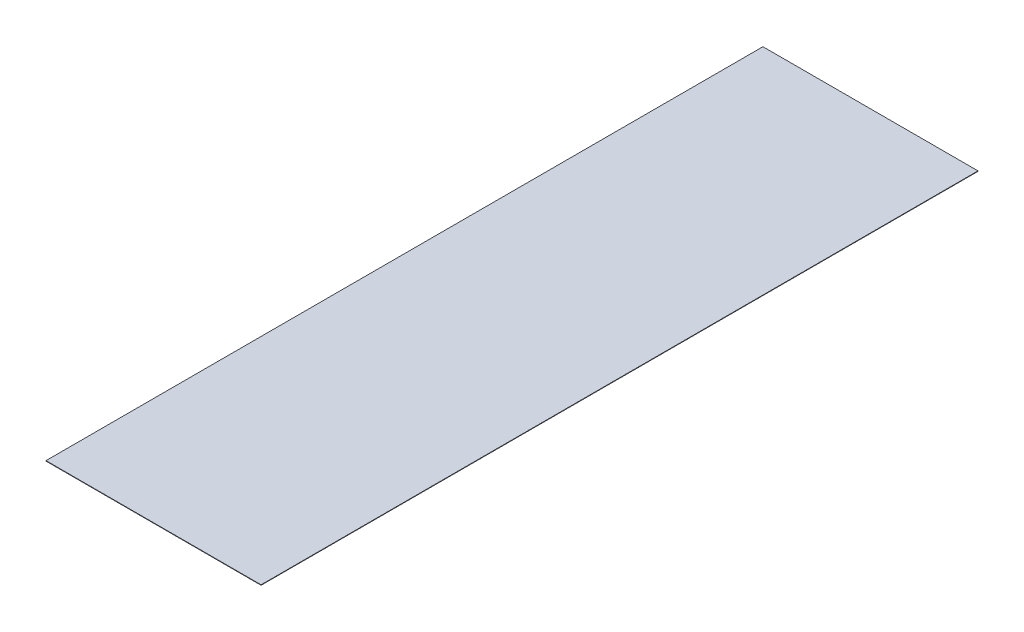
SolidWorks part; units mm, degrees
material "ASTM A36 Acero"
ref_plane "Alzado" through (0, 0, 0) normal (0, 0, 1) x (1, 0, 0)
ref_plane "Planta" through (0, 0, 0) normal (0, 1, 0) x (1, 0, 0)
ref_plane "Vista lateral" through (0, 0, 0) normal (1, 0, 0) x (0, 0, -1)
sketch "Croquis1" plane through (0, 0, 0) normal (0, 1, 0) x (1, 0, 0)
  line L1 (-457.2, -1524) -> (457.2, -1524)
  line L2 (-457.2, -1524) -> (-457.2, 1524)
  line L3 (-457.2, 1524) -> (457.2, 1524)
  line L4 (457.2, -1524) -> (457.2, 1524)
  line L5 (-457.2, -1524) -> (457.2, 1524) construction
  line L6 (-457.2, 1524) -> (457.2, -1524) construction
  point P0 (0, 0)
  dimension "D1" = 3048
  dimension "D2" = 914.4
extrude "Saliente-Extruir1" add sketch "Croquis1" along normal blind 1.9
